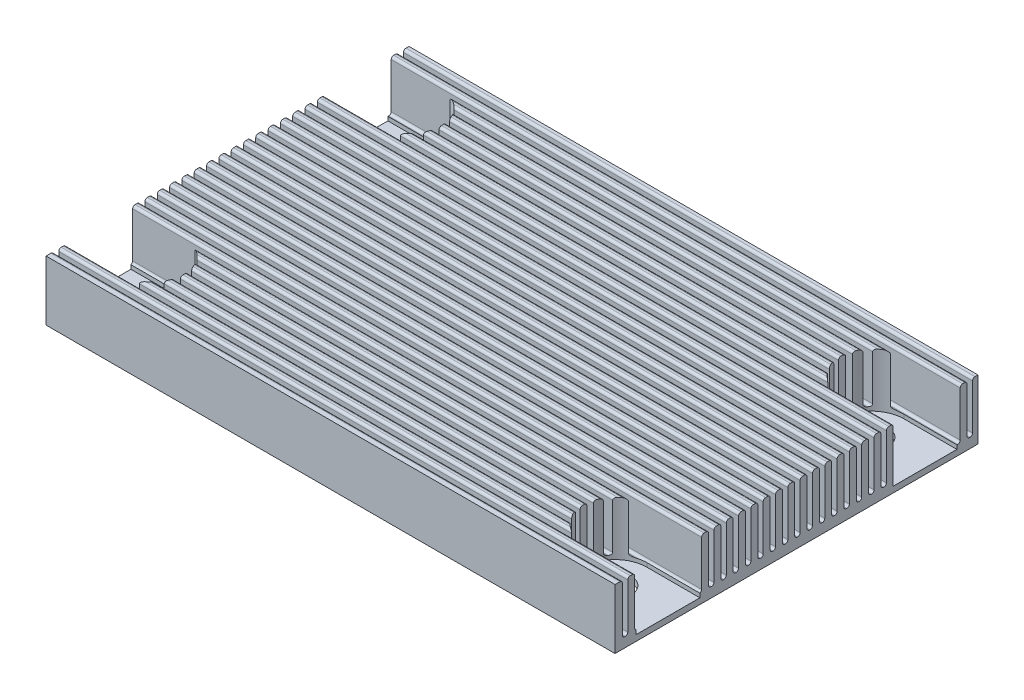
SolidWorks part; units mm, degrees
ref_plane "Front Plane" through (0, 0, 0) normal (0, 0, 1) x (1, 0, 0)
ref_plane "Top Plane" through (0, 0, 0) normal (0, 1, 0) x (1, 0, 0)
ref_plane "Right Plane" through (0, 0, 0) normal (1, 0, 0) x (0, 0, -1)
sketch "Sketch1" plane through (0, 0, 0) normal (0, 1, 0) x (1, 0, 0)
  line L1 (-29, -18.5) -> (29, -18.5)
  line L2 (-29, -18.5) -> (-29, 18.5)
  line L3 (-29, 18.5) -> (29, 18.5)
  line L4 (29, -18.5) -> (29, 18.5)
  line L5 (-29, -18.5) -> (29, 18.5) construction
  line L6 (-29, 18.5) -> (29, -18.5) construction
  line L7 (-23.6, -13.1) -> (23.6, -13.1) construction
  line L8 (-23.6, -13.1) -> (-23.6, 13.1) construction
  line L9 (-23.6, 13.1) -> (23.6, 13.1) construction
  line L10 (23.6, -13.1) -> (23.6, 13.1) construction
  line L11 (-23.6, -13.1) -> (23.6, 13.1) construction
  line L12 (-23.6, 13.1) -> (23.6, -13.1) construction
  circle A0 centre (-23.6, 13.1) radius 1.65
  circle A1 centre (-23.6, -13.1) radius 1.65
  circle A2 centre (23.6, -13.1) radius 1.65
  circle A3 centre (23.6, 13.1) radius 1.65
  point P0 (0, 0)
  point P6 (0, 0)
  dimension "D5" = 3.3
  dimension "D1" = 58
  dimension "D2" = 37
  dimension "D3" = 47.2
  dimension "D4" = 26.2
extrude "Boss-Extrude1" add sketch "Sketch1" along normal blind 6.1
sketch "Sketch2" plane through (29, 0, 0) normal (1, 0, 0) x (0, 0, -1)
  line L0 (-17.75, 5.85) -> (-17.75, 1.25)
  line L1 (-18.5, 6.1) -> (18.5, 6.1) construction
  line L2 (-17.5, 1) -> (-17.45, 1)
  line L3 (-17.2, 1.25) -> (-17.2, 5.85)
  line L4 (-18, 6.1) -> (-18.5, 6.1)
  line L5 (-18.5, 0) -> (18.5, 0) construction
  line L7 (-16.95, 6.1) -> (-16.7, 6.1)
  line L8 (-16.495, 5.85) -> (-16.495, 1.25)
  line L9 (-15.945, 1.25) -> (-15.945, 5.85)
  line L10 (-15.695, 6.1) -> (-15.445, 6.1)
  line L11 (-16.245, 1) -> (-16.195, 1)
  line L12 (-15.24, 5.85) -> (-15.24, 1.25)
  line L13 (-14.69, 1.25) -> (-14.69, 5.85)
  line L14 (-14.44, 6.1) -> (-14.19, 6.1)
  line L15 (-14.99, 1) -> (-14.94, 1)
  line L16 (-13.985, 5.85) -> (-13.985, 1.25)
  line L17 (-13.435, 1.25) -> (-13.435, 5.85)
  line L18 (-13.185, 6.1) -> (-12.935, 6.1)
  line L19 (-13.735, 1) -> (-13.685, 1)
  line L20 (-12.73, 5.85) -> (-12.73, 1.25)
  line L21 (-12.18, 1.25) -> (-12.18, 5.85)
  line L22 (-11.93, 6.1) -> (-11.68, 6.1)
  line L23 (-12.48, 1) -> (-12.43, 1)
  line L24 (-11.475, 5.85) -> (-11.475, 1.25)
  line L25 (-10.925, 1.25) -> (-10.925, 5.85)
  line L26 (-10.675, 6.1) -> (-10.425, 6.1)
  line L27 (-11.225, 1) -> (-11.175, 1)
  line L28 (-10.22, 5.85) -> (-10.22, 1.25)
  line L29 (-9.67, 1.25) -> (-9.67, 5.85)
  line L30 (-9.42, 6.1) -> (-9.17, 6.1)
  line L31 (-9.97, 1) -> (-9.92, 1)
  line L32 (-8.965, 5.85) -> (-8.965, 1.25)
  line L33 (-8.415, 1.25) -> (-8.415, 5.85)
  line L34 (-8.165, 6.1) -> (-7.915, 6.1)
  line L35 (-8.715, 1) -> (-8.665, 1)
  line L36 (-7.71, 5.85) -> (-7.71, 1.25)
  line L37 (-7.16, 1.25) -> (-7.16, 5.85)
  line L38 (-6.91, 6.1) -> (-6.66, 6.1)
  line L39 (-7.46, 1) -> (-7.41, 1)
  line L40 (-6.455, 5.85) -> (-6.455, 1.25)
  line L41 (-5.905, 1.25) -> (-5.905, 5.85)
  line L42 (-5.655, 6.1) -> (-5.405, 6.1)
  line L43 (-6.205, 1) -> (-6.155, 1)
  line L44 (-5.2, 5.85) -> (-5.2, 1.25)
  line L45 (-4.65, 1.25) -> (-4.65, 5.85)
  line L46 (-4.4, 6.1) -> (-4.15, 6.1)
  line L47 (-4.95, 1) -> (-4.9, 1)
  line L48 (-3.945, 5.85) -> (-3.945, 1.25)
  line L49 (-3.395, 1.25) -> (-3.395, 5.85)
  line L50 (-3.145, 6.1) -> (-2.895, 6.1)
  line L51 (-3.695, 1) -> (-3.645, 1)
  line L52 (-2.69, 5.85) -> (-2.69, 1.25)
  line L53 (-2.14, 1.25) -> (-2.14, 5.85)
  line L54 (-1.89, 6.1) -> (-1.64, 6.1)
  line L55 (-2.44, 1) -> (-2.39, 1)
  line L56 (-1.435, 5.85) -> (-1.435, 1.25)
  line L57 (-0.885, 1.25) -> (-0.885, 5.85)
  line L58 (-0.635, 6.1) -> (-0.385, 6.1)
  line L59 (-1.185, 1) -> (-1.135, 1)
  line L60 (-0.18, 5.85) -> (-0.18, 1.25)
  line L61 (0.37, 1.25) -> (0.37, 5.85)
  line L62 (0.62, 6.1) -> (0.87, 6.1)
  line L63 (0.07, 1) -> (0.12, 1)
  line L64 (1.075, 5.85) -> (1.075, 1.25)
  line L65 (1.625, 1.25) -> (1.625, 5.85)
  line L66 (1.875, 6.1) -> (2.125, 6.1)
  line L67 (1.325, 1) -> (1.375, 1)
  line L68 (2.33, 5.85) -> (2.33, 1.25)
  line L69 (2.88, 1.25) -> (2.88, 5.85)
  line L70 (3.13, 6.1) -> (3.38, 6.1)
  line L71 (2.58, 1) -> (2.63, 1)
  line L72 (3.585, 5.85) -> (3.585, 1.25)
  line L73 (4.135, 1.25) -> (4.135, 5.85)
  line L74 (4.385, 6.1) -> (4.635, 6.1)
  line L75 (3.835, 1) -> (3.885, 1)
  line L76 (4.84, 5.85) -> (4.84, 1.25)
  line L77 (5.39, 1.25) -> (5.39, 5.85)
  line L78 (5.64, 6.1) -> (5.89, 6.1)
  line L79 (5.09, 1) -> (5.14, 1)
  line L80 (6.095, 5.85) -> (6.095, 1.25)
  line L81 (6.645, 1.25) -> (6.645, 5.85)
  line L82 (6.895, 6.1) -> (7.145, 6.1)
  line L83 (6.345, 1) -> (6.395, 1)
  line L84 (7.35, 5.85) -> (7.35, 1.25)
  line L85 (7.9, 1.25) -> (7.9, 5.85)
  line L86 (8.15, 6.1) -> (8.4, 6.1)
  line L87 (7.6, 1) -> (7.65, 1)
  line L88 (8.605, 5.85) -> (8.605, 1.25)
  line L89 (9.155, 1.25) -> (9.155, 5.85)
  line L90 (9.405, 6.1) -> (9.655, 6.1)
  line L91 (8.855, 1) -> (8.905, 1)
  line L92 (9.86, 5.85) -> (9.86, 1.25)
  line L93 (10.41, 1.25) -> (10.41, 5.85)
  line L94 (10.66, 6.1) -> (10.91, 6.1)
  line L95 (10.11, 1) -> (10.16, 1)
  line L96 (11.115, 5.85) -> (11.115, 1.25)
  line L97 (11.665, 1.25) -> (11.665, 5.85)
  line L98 (11.915, 6.1) -> (12.165, 6.1)
  line L99 (11.365, 1) -> (11.415, 1)
  line L100 (12.37, 5.85) -> (12.37, 1.25)
  line L101 (12.92, 1.25) -> (12.92, 5.85)
  line L102 (13.17, 6.1) -> (13.42, 6.1)
  line L103 (12.62, 1) -> (12.67, 1)
  line L104 (13.625, 5.85) -> (13.625, 1.25)
  line L105 (14.175, 1.25) -> (14.175, 5.85)
  line L106 (14.425, 6.1) -> (14.675, 6.1)
  line L107 (13.875, 1) -> (13.925, 1)
  line L108 (14.88, 5.85) -> (14.88, 1.25)
  line L109 (15.43, 1.25) -> (15.43, 5.85)
  line L110 (15.68, 6.1) -> (15.93, 6.1)
  line L111 (15.13, 1) -> (15.18, 1)
  line L112 (16.135, 5.85) -> (16.135, 1.25)
  line L113 (16.685, 1.25) -> (16.685, 5.85)
  line L114 (16.935, 6.1) -> (17.185, 6.1)
  line L115 (16.385, 1) -> (16.435, 1)
  line L116 (17.39, 5.85) -> (17.39, 1.25)
  line L117 (17.94, 1.25) -> (17.94, 5.85)
  line L118 (18.19, 6.1) -> (18.44, 6.1)
  line L119 (17.64, 1) -> (17.69, 1)
  line L120 (-17.75, 5.85) -> (-16.495, 5.85) construction
  line L121 (18.44, 6.1) -> (18.5, 6.1)
  line L122 (18.5, 6.1) -> (18.5, 0)
  line L123 (18.5, 0) -> (-18.5, 0)
  line L124 (-18.5, 0) -> (-18.5, 6.1)
  line L125 (-18.5, 6.1) -> (18.5, 6.1)
  arc A0 (-17.45, 1) -> (-17.2, 1.25) centre (-17.45, 1.25) ccw
  arc A1 (-17.75, 1.25) -> (-17.5, 1) centre (-17.5, 1.25) ccw
  arc A2 (-17.75, 5.85) -> (-18, 6.1) centre (-18, 5.85) ccw
  arc A3 (-17.2, 5.85) -> (-16.95, 6.1) centre (-16.95, 5.85) cw
  arc A4 (-16.495, 1.25) -> (-16.245, 1) centre (-16.245, 1.25) ccw
  arc A5 (-16.195, 1) -> (-15.945, 1.25) centre (-16.195, 1.25) ccw
  arc A6 (-15.945, 5.85) -> (-15.695, 6.1) centre (-15.695, 5.85) cw
  arc A7 (-16.495, 5.85) -> (-16.745, 6.1) centre (-16.745, 5.85) ccw
  arc A8 (-15.24, 1.25) -> (-14.99, 1) centre (-14.99, 1.25) ccw
  arc A9 (-14.94, 1) -> (-14.69, 1.25) centre (-14.94, 1.25) ccw
  arc A10 (-14.69, 5.85) -> (-14.44, 6.1) centre (-14.44, 5.85) cw
  arc A11 (-15.24, 5.85) -> (-15.49, 6.1) centre (-15.49, 5.85) ccw
  arc A12 (-13.985, 1.25) -> (-13.735, 1) centre (-13.735, 1.25) ccw
  arc A13 (-13.685, 1) -> (-13.435, 1.25) centre (-13.685, 1.25) ccw
  arc A14 (-13.435, 5.85) -> (-13.185, 6.1) centre (-13.185, 5.85) cw
  arc A15 (-13.985, 5.85) -> (-14.235, 6.1) centre (-14.235, 5.85) ccw
  arc A16 (-12.73, 1.25) -> (-12.48, 1) centre (-12.48, 1.25) ccw
  arc A17 (-12.43, 1) -> (-12.18, 1.25) centre (-12.43, 1.25) ccw
  arc A18 (-12.18, 5.85) -> (-11.93, 6.1) centre (-11.93, 5.85) cw
  arc A19 (-12.73, 5.85) -> (-12.98, 6.1) centre (-12.98, 5.85) ccw
  arc A20 (-11.475, 1.25) -> (-11.225, 1) centre (-11.225, 1.25) ccw
  arc A21 (-11.175, 1) -> (-10.925, 1.25) centre (-11.175, 1.25) ccw
  arc A22 (-10.925, 5.85) -> (-10.675, 6.1) centre (-10.675, 5.85) cw
  arc A23 (-11.475, 5.85) -> (-11.725, 6.1) centre (-11.725, 5.85) ccw
  arc A24 (-10.22, 1.25) -> (-9.97, 1) centre (-9.97, 1.25) ccw
  arc A25 (-9.92, 1) -> (-9.67, 1.25) centre (-9.92, 1.25) ccw
  arc A26 (-9.67, 5.85) -> (-9.42, 6.1) centre (-9.42, 5.85) cw
  arc A27 (-10.22, 5.85) -> (-10.47, 6.1) centre (-10.47, 5.85) ccw
  arc A28 (-8.965, 1.25) -> (-8.715, 1) centre (-8.715, 1.25) ccw
  arc A29 (-8.665, 1) -> (-8.415, 1.25) centre (-8.665, 1.25) ccw
  arc A30 (-8.415, 5.85) -> (-8.165, 6.1) centre (-8.165, 5.85) cw
  arc A31 (-8.965, 5.85) -> (-9.215, 6.1) centre (-9.215, 5.85) ccw
  arc A32 (-7.71, 1.25) -> (-7.46, 1) centre (-7.46, 1.25) ccw
  arc A33 (-7.41, 1) -> (-7.16, 1.25) centre (-7.41, 1.25) ccw
  arc A34 (-7.16, 5.85) -> (-6.91, 6.1) centre (-6.91, 5.85) cw
  arc A35 (-7.71, 5.85) -> (-7.96, 6.1) centre (-7.96, 5.85) ccw
  arc A36 (-6.455, 1.25) -> (-6.205, 1) centre (-6.205, 1.25) ccw
  arc A37 (-6.155, 1) -> (-5.905, 1.25) centre (-6.155, 1.25) ccw
  arc A38 (-5.905, 5.85) -> (-5.655, 6.1) centre (-5.655, 5.85) cw
  arc A39 (-6.455, 5.85) -> (-6.705, 6.1) centre (-6.705, 5.85) ccw
  arc A40 (-5.2, 1.25) -> (-4.95, 1) centre (-4.95, 1.25) ccw
  arc A41 (-4.9, 1) -> (-4.65, 1.25) centre (-4.9, 1.25) ccw
  arc A42 (-4.65, 5.85) -> (-4.4, 6.1) centre (-4.4, 5.85) cw
  arc A43 (-5.2, 5.85) -> (-5.45, 6.1) centre (-5.45, 5.85) ccw
  arc A44 (-3.945, 1.25) -> (-3.695, 1) centre (-3.695, 1.25) ccw
  arc A45 (-3.645, 1) -> (-3.395, 1.25) centre (-3.645, 1.25) ccw
  arc A46 (-3.395, 5.85) -> (-3.145, 6.1) centre (-3.145, 5.85) cw
  arc A47 (-3.945, 5.85) -> (-4.195, 6.1) centre (-4.195, 5.85) ccw
  arc A48 (-2.69, 1.25) -> (-2.44, 1) centre (-2.44, 1.25) ccw
  arc A49 (-2.39, 1) -> (-2.14, 1.25) centre (-2.39, 1.25) ccw
  arc A50 (-2.14, 5.85) -> (-1.89, 6.1) centre (-1.89, 5.85) cw
  arc A51 (-2.69, 5.85) -> (-2.94, 6.1) centre (-2.94, 5.85) ccw
  arc A52 (-1.435, 1.25) -> (-1.185, 1) centre (-1.185, 1.25) ccw
  arc A53 (-1.135, 1) -> (-0.885, 1.25) centre (-1.135, 1.25) ccw
  arc A54 (-0.885, 5.85) -> (-0.635, 6.1) centre (-0.635, 5.85) cw
  arc A55 (-1.435, 5.85) -> (-1.685, 6.1) centre (-1.685, 5.85) ccw
  arc A56 (-0.18, 1.25) -> (0.07, 1) centre (0.07, 1.25) ccw
  arc A57 (0.12, 1) -> (0.37, 1.25) centre (0.12, 1.25) ccw
  arc A58 (0.37, 5.85) -> (0.62, 6.1) centre (0.62, 5.85) cw
  arc A59 (-0.18, 5.85) -> (-0.43, 6.1) centre (-0.43, 5.85) ccw
  arc A60 (1.075, 1.25) -> (1.325, 1) centre (1.325, 1.25) ccw
  arc A61 (1.375, 1) -> (1.625, 1.25) centre (1.375, 1.25) ccw
  arc A62 (1.625, 5.85) -> (1.875, 6.1) centre (1.875, 5.85) cw
  arc A63 (1.075, 5.85) -> (0.825, 6.1) centre (0.825, 5.85) ccw
  arc A64 (2.33, 1.25) -> (2.58, 1) centre (2.58, 1.25) ccw
  arc A65 (2.63, 1) -> (2.88, 1.25) centre (2.63, 1.25) ccw
  arc A66 (2.88, 5.85) -> (3.13, 6.1) centre (3.13, 5.85) cw
  arc A67 (2.33, 5.85) -> (2.08, 6.1) centre (2.08, 5.85) ccw
  arc A68 (3.585, 1.25) -> (3.835, 1) centre (3.835, 1.25) ccw
  arc A69 (3.885, 1) -> (4.135, 1.25) centre (3.885, 1.25) ccw
  arc A70 (4.135, 5.85) -> (4.385, 6.1) centre (4.385, 5.85) cw
  arc A71 (3.585, 5.85) -> (3.335, 6.1) centre (3.335, 5.85) ccw
  arc A72 (4.84, 1.25) -> (5.09, 1) centre (5.09, 1.25) ccw
  arc A73 (5.14, 1) -> (5.39, 1.25) centre (5.14, 1.25) ccw
  arc A74 (5.39, 5.85) -> (5.64, 6.1) centre (5.64, 5.85) cw
  arc A75 (4.84, 5.85) -> (4.59, 6.1) centre (4.59, 5.85) ccw
  arc A76 (6.095, 1.25) -> (6.345, 1) centre (6.345, 1.25) ccw
  arc A77 (6.395, 1) -> (6.645, 1.25) centre (6.395, 1.25) ccw
  arc A78 (6.645, 5.85) -> (6.895, 6.1) centre (6.895, 5.85) cw
  arc A79 (6.095, 5.85) -> (5.845, 6.1) centre (5.845, 5.85) ccw
  arc A80 (7.35, 1.25) -> (7.6, 1) centre (7.6, 1.25) ccw
  arc A81 (7.65, 1) -> (7.9, 1.25) centre (7.65, 1.25) ccw
  arc A82 (7.9, 5.85) -> (8.15, 6.1) centre (8.15, 5.85) cw
  arc A83 (7.35, 5.85) -> (7.1, 6.1) centre (7.1, 5.85) ccw
  arc A84 (8.605, 1.25) -> (8.855, 1) centre (8.855, 1.25) ccw
  arc A85 (8.905, 1) -> (9.155, 1.25) centre (8.905, 1.25) ccw
  arc A86 (9.155, 5.85) -> (9.405, 6.1) centre (9.405, 5.85) cw
  arc A87 (8.605, 5.85) -> (8.355, 6.1) centre (8.355, 5.85) ccw
  arc A88 (9.86, 1.25) -> (10.11, 1) centre (10.11, 1.25) ccw
  arc A89 (10.16, 1) -> (10.41, 1.25) centre (10.16, 1.25) ccw
  arc A90 (10.41, 5.85) -> (10.66, 6.1) centre (10.66, 5.85) cw
  arc A91 (9.86, 5.85) -> (9.61, 6.1) centre (9.61, 5.85) ccw
  arc A92 (11.115, 1.25) -> (11.365, 1) centre (11.365, 1.25) ccw
  arc A93 (11.415, 1) -> (11.665, 1.25) centre (11.415, 1.25) ccw
  arc A94 (11.665, 5.85) -> (11.915, 6.1) centre (11.915, 5.85) cw
  arc A95 (11.115, 5.85) -> (10.865, 6.1) centre (10.865, 5.85) ccw
  arc A96 (12.37, 1.25) -> (12.62, 1) centre (12.62, 1.25) ccw
  arc A97 (12.67, 1) -> (12.92, 1.25) centre (12.67, 1.25) ccw
  arc A98 (12.92, 5.85) -> (13.17, 6.1) centre (13.17, 5.85) cw
  arc A99 (12.37, 5.85) -> (12.12, 6.1) centre (12.12, 5.85) ccw
  arc A100 (13.625, 1.25) -> (13.875, 1) centre (13.875, 1.25) ccw
  arc A101 (13.925, 1) -> (14.175, 1.25) centre (13.925, 1.25) ccw
  arc A102 (14.175, 5.85) -> (14.425, 6.1) centre (14.425, 5.85) cw
  arc A103 (13.625, 5.85) -> (13.375, 6.1) centre (13.375, 5.85) ccw
  arc A104 (14.88, 1.25) -> (15.13, 1) centre (15.13, 1.25) ccw
  arc A105 (15.18, 1) -> (15.43, 1.25) centre (15.18, 1.25) ccw
  arc A106 (15.43, 5.85) -> (15.68, 6.1) centre (15.68, 5.85) cw
  arc A107 (14.88, 5.85) -> (14.63, 6.1) centre (14.63, 5.85) ccw
  arc A108 (16.135, 1.25) -> (16.385, 1) centre (16.385, 1.25) ccw
  arc A109 (16.435, 1) -> (16.685, 1.25) centre (16.435, 1.25) ccw
  arc A110 (16.685, 5.85) -> (16.935, 6.1) centre (16.935, 5.85) cw
  arc A111 (16.135, 5.85) -> (15.885, 6.1) centre (15.885, 5.85) ccw
  arc A112 (17.39, 1.25) -> (17.64, 1) centre (17.64, 1.25) ccw
  arc A113 (17.69, 1) -> (17.94, 1.25) centre (17.69, 1.25) ccw
  arc A114 (17.94, 5.85) -> (18.19, 6.1) centre (18.19, 5.85) cw
  arc A115 (17.39, 5.85) -> (17.14, 6.1) centre (17.14, 5.85) ccw
  point P14 (-17.75, 6.1)
  line M236 (18.5, 6.1) -> (-18.5, 6.1)
  dimension "D1" = 0.25
  dimension "D2" = 0.25
  dimension "D6" = 0.5
  dimension "D3" = 1.25
  dimension "D4" = 0.55
  dimension "D5" = 0.5
  dimension "D8" = 1.255
  dimension "D7" = 29
extrude "Cut-Extrude1" cut sketch "Sketch2" against normal through all contours A23 L24 A20 L27 A21 L25 A22 M236 | A27 L28 A24 L31 A25 L29 A26 M236 | A31 L32 A28 L35 A29 L33 A30 M236 | A35 L36 A32 L39 A33 L37 A34 M236 | A39 L40 A36 L43 A37 L41 A38 M236 | A19 L20 A16 L23 A17 L21 A18 M236 | A15 L16 A12 L19 A13 L17 A14 M236 | A11 L12 A8 L15 A9 L13 A10 M236 | A7 L8 A4 L11 A5 L9 A6 M236 | L120 L0 A1 L2 A0 L3 | A2 L120 A3 M236 | A43 L44 A40 L47 A41 L45 A42 M236 | A47 L48 A44 L51 A45 L49 A46 M236 | A51 L52 A48 L55 A49 L53 A50 M236 | A55 L56 A52 L59 A53 L57 A54 M236 | A59 L60 A56 L63 A57 L61 A58 M236 | A63 L64 A60 L67 A61 L65 A62 M236 | A67 L68 A64 L71 A65 L69 A66 M236 | A71 L72 A68 L75 A69 L73 A70 M236 | A75 L76 A72 L79 A73 L77 A74 M236 | A79 L80 A76 L83 A77 L81 A78 M236 | A83 L84 A80 L87 A81 L85 A82 M236 | A87 L88 A84 L91 A85 L89 A86 M236 | A91 L92 A88 L95 A89 L93 A90 M236 | A95 L96 A92 L99 A93 L97 A94 M236 | A99 L100 A96 L103 A97 L101 A98 M236 | A103 L104 A100 L107 A101 L105 A102 M236 | A107 L108 A104 L111 A105 L109 A106 M236 | A111 L112 A108 L115 A109 L113 A110 M236 | A115 L116 A112 L119 A113 L117 A114 M236
sketch "Sketch3" plane through (0, 6.1, 0) normal (0, 1, 0) x (1, 0, 0)
  line L0 (-29, 18.5) -> (-29, -18.5) construction
  line L1 (29, -18.5) -> (29, 18.5) construction
  line L2 (-29, 16.35) -> (-29, 9.85)
  line L3 (29, -16.35) -> (29, -9.85)
  line L4 (-23.6, 16.35) -> (-29, 16.35)
  line L5 (-23.6, 9.85) -> (-29, 9.85)
  line L6 (-23.6, -9.85) -> (-29, -9.85)
  line L7 (-23.6, -16.35) -> (-29, -16.35)
  line L8 (-29, -9.85) -> (-29, -16.35)
  line L9 (23.6, 16.35) -> (29, 16.35)
  line L10 (23.6, 9.85) -> (29, 9.85)
  line L11 (23.6, -9.85) -> (29, -9.85)
  line L12 (29, -9.85) -> (29, -16.35)
  line L13 (29, -16.35) -> (23.6, -16.35)
  line L14 (29, 9.85) -> (29, 16.35)
  circle A0 centre (-23.6, 13.1) radius 1.65 construction
  circle A1 centre (-23.6, -13.1) radius 1.65 construction
  circle A3 centre (23.6, -13.1) radius 1.65 construction
  circle A4 centre (23.6, 13.1) radius 1.65 construction
  circle A5 centre (23.6, -13.1) radius 1.65 construction
  circle A6 centre (-23.6, -13.1) radius 1.65 construction
  circle A7 centre (-23.6, 13.1) radius 1.65 construction
  circle A8 centre (23.6, 13.1) radius 1.65 construction
  circle A9 centre (-23.6, 13.1) radius 3.25
  circle A10 centre (23.6, 13.1) radius 3.25
  circle A11 centre (23.6, -13.1) radius 3.25
  circle A12 centre (-23.6, -13.1) radius 3.25
  line M8 (-24.2177, 14.63) -> (-29, 14.63)
  line M9 (-29, 14.63) -> (-29, 14.425)
  line M10 (-29, 14.425) -> (-24.5833, 14.425)
  arc M11 (-24.5833, 14.425) -> (-24.2177, 14.63) centre (-23.6, 13.1) cw
  dimension "D1" = 6.5
extrude "Cut-Extrude3" cut sketch "Sketch3" against normal blind 5.5 contours A9 L2 L5 M10 | A9 L4 L2 M8 | A9 M8 M11 M10 | A12 | A12 L6 L8 L7 | A11 | A11 L13 L3 L11 | A10 L10 L14 L9 | A10 | A9 M8 M9 M10 | A9 M8 M10 M11
